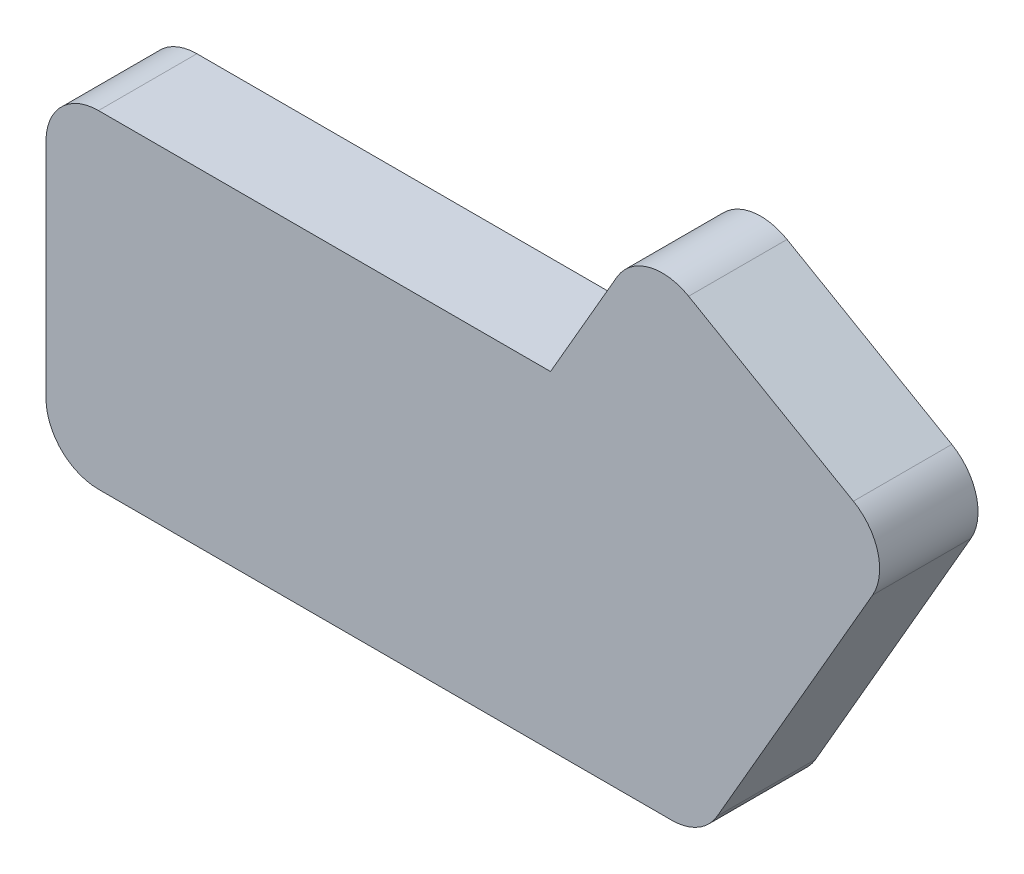
SolidWorks part; units mm, degrees
ref_plane "Front Plane" through (0, 0, 0) normal (0, 0, 1) x (1, 0, 0)
ref_plane "Top Plane" through (0, 0, 0) normal (0, 1, 0) x (1, 0, 0)
ref_plane "Right Plane" through (0, 0, 0) normal (1, 0, 0) x (0, 0, -1)
sketch "Sketch1" plane through (0, 0, 0) normal (0, 0, 1) x (1, 0, 0)
  line L0 (8, 0) -> (95.3812, 0)
  line L1 (102.3094, 4) -> (126, 45.0333)
  line L2 (123.0718, 55.9615) -> (97.9571, 70.4615)
  line L3 (87.0289, 67.5333) -> (76.906, 50)
  line L4 (76.906, 50) -> (8, 50)
  line L5 (0, 42) -> (0, 8)
  arc A0 (97.9571, 70.4615) -> (87.0289, 67.5333) centre (93.9571, 63.5333) ccw
  arc A1 (8, 50) -> (0, 42) centre (8, 42) ccw
  arc A2 (0, 8) -> (8, 0) centre (8, 8) ccw
  arc A3 (95.3812, 0) -> (102.3094, 4) centre (95.3812, 8) ccw
  arc A4 (126, 45.0333) -> (123.0718, 55.9615) centre (119.0718, 49.0333) ccw
  point P3 (0, 0)
  point P8 (0, 0)
  point P9 (0, 0)
  point P10 (0, 0)
  point P13 (91.0289, 74.4615)
  point P16 (0, 50)
  point P19 (0, 0)
  point P22 (100, 0)
  point P25 (130, 51.9615)
  dimension "D6" = 8
  dimension "D7" = 8
  dimension "D1" = 45
  dimension "D2" = 100
  dimension "D3" = 130
  dimension "D4" = 50
  dimension "D5" = 120
extrude "Boss-Extrude1" add sketch "Sketch1" along normal blind 15
